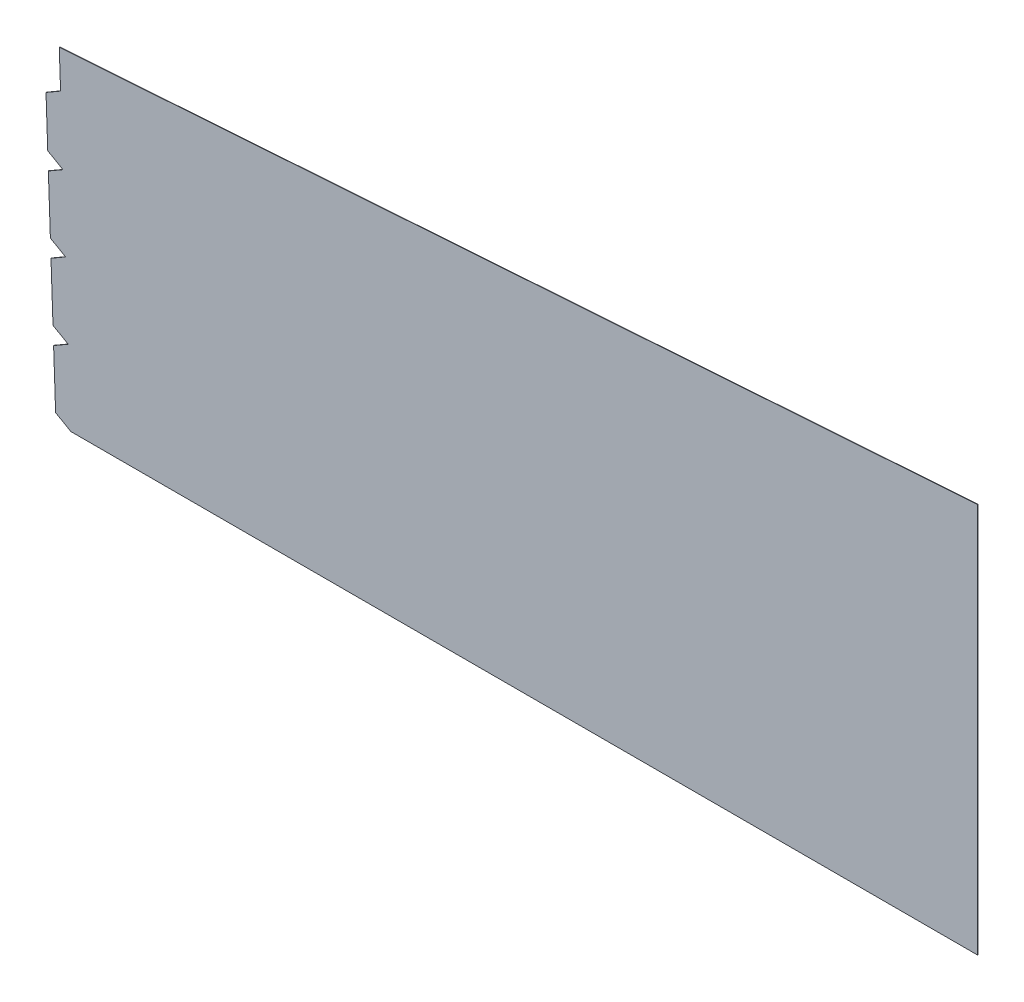
SolidWorks part; units mm, degrees
ref_plane "front" through (0, 0, 0) normal (0, 0, 1) x (1, 0, 0)
ref_plane "top" through (0, 0, 0) normal (0, 1, 0) x (1, 0, 0)
ref_plane "right" through (0, 0, 0) normal (1, 0, 0) x (0, 0, -1)
sketch "Sketch1" plane through (0, 0, 0) normal (0, 0, 1) x (1, 0, 0)
  line L1 (0, 0) -> (1549.4, 0)
  line L2 (0, 0) -> (-17.4752, 494.9916) construction
  line L3 (-19.7279, 558.8) -> (1549.4, 666.75)
  line L4 (1549.4, 0) -> (1549.4, 666.75)
  line L5 (1499.4889, 609.511) -> (-17.9233, 507.6837) construction
  line L6 (0, 0) -> (-25.9446, 14.9791)
  line L7 (-25.9446, 14.9791) -> (-29.3889, 112.5402)
  line L8 (-29.3889, 112.5402) -> (-4.4808, 126.9209)
  line L9 (-4.4808, 126.9209) -> (-30.4255, 141.9001)
  line L10 (-30.4255, 141.9001) -> (-33.8698, 239.4611)
  line L11 (-33.8698, 239.4611) -> (-8.9616, 253.8419)
  line L12 (-8.9616, 253.8419) -> (-34.9063, 268.821)
  line L13 (-34.9063, 268.821) -> (-38.3506, 366.3821)
  line L14 (-38.3506, 366.3821) -> (-13.4425, 380.7628)
  line L15 (-13.4425, 380.7628) -> (-39.3871, 395.7419)
  line L16 (-39.3871, 395.7419) -> (-42.3833, 480.6109)
  line L17 (-42.3833, 480.6109) -> (-17.4752, 494.9916)
  line L18 (-17.4752, 494.9916) -> (-19.7279, 558.8)
  line L19 (1489.075, 0) -> (1499.4889, 609.511) construction
  line L20 (1489.075, 0) -> (1489.075, 187.2029) construction
  point P21 (1499.4889, 609.511)
  dimension "D1" = 1549.4
  dimension "D2" = 666.75
  dimension "D3" = 609.6
  dimension "D5" = 17.4752
  dimension "D6" = 558.8
  dimension "D7" = 10.4139
  dimension "D8" = 25.4
  dimension "D9" = 30
  dimension "D10" = 30
  dimension "D11" = 127
  dimension "D12" = 127
  dimension "D13" = 127
  dimension "D14" = 114.3
  dimension "D15" = 42.3833
  dimension "D16" = 1489.075
  dimension "D17" = 1591.7833
  dimension "D18" = 508
  dimension "D20" = 1520.825
extrude "Extrude1" add sketch "Sketch1" along normal blind 0.762
